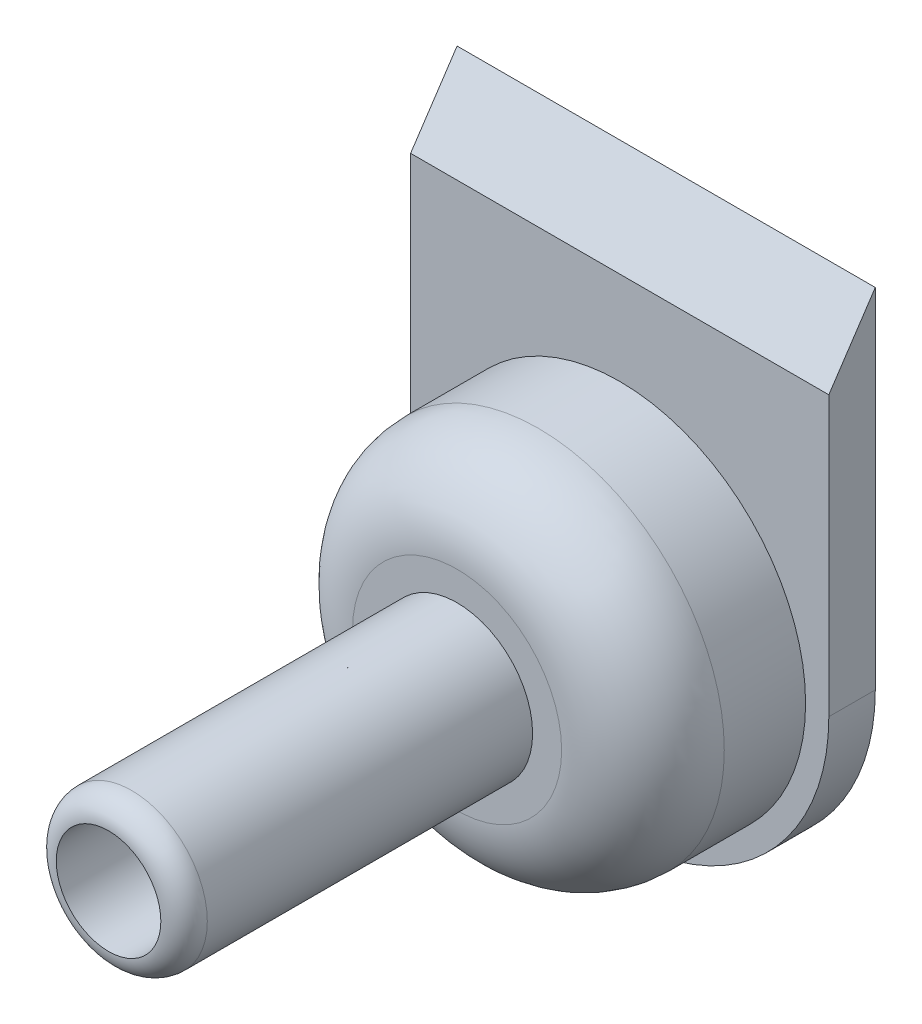
SolidWorks part; units mm, degrees
ref_plane "Płaszczyzna przednia" through (0, 0, 0) normal (0, 0, 1) x (1, 0, 0)
ref_plane "Płaszczyzna górna" through (0, 0, 0) normal (0, 1, 0) x (1, 0, 0)
ref_plane "Płaszczyzna prawa" through (0, 0, 0) normal (1, 0, 0) x (0, 0, -1)
sketch "Szkic1" plane through (0, 0, 0) normal (0, 0, 1) x (1, 0, 0)
  circle A0 centre (0, 0) radius 6.5
  dimension "D1" = 13
extrude "Dodanie-wyciągnięcie1" add sketch "Szkic1" along normal blind 30
fillet "Zaokrąglenie1" radius 2 1 edges at (6.5, 0, 30)
sketch "Szkic2" plane through (0, 0, 0) normal (0, 0, -1) x (-1, 0, 0)
  circle A0 centre (0, 0) radius 4.5
  dimension "D1" = 9
extrude "Wytnij-wyciągnięcie1" cut sketch "Szkic2" against normal blind 30
sketch "Szkic3" plane through (0, 0, 0) normal (0, 0, -1) x (-1, 0, 0)
  circle A0 centre (0, 0) radius 16
  dimension "D1" = 32
extrude "Dodanie-wyciągnięcie2" add sketch "Szkic3" along normal blind 14
fillet "Zaokrąglenie2" radius 7 1 edges at (-16, 0, 0)
sketch "Szkic4" plane through (0, 0, -14) normal (0, 0, -1) x (-1, 0, 0)
  circle A0 centre (0, 0) radius 18
  dimension "D1" = 36
extrude "Dodanie-wyciągnięcie3" add sketch "Szkic4" along normal blind 4
ref_plane "Płaszczyzna1" through (0, 30, 0) normal (0, 1, 0) x (1, 0, 0)
sketch "Szkic5" plane through (0, 30, 0) normal (0, 1, 0) x (1, 0, 0)
  line L1 (18, 14) -> (-18, 14)
  line L2 (18, 14) -> (18, 18)
  line L3 (18, 18) -> (-18, 18)
  line L4 (-18, 14) -> (-18, 18)
extrude "Dodanie-wyciągnięcie4" add sketch "Szkic5" against normal up to next
sketch "Szkic6" plane through (18, 0, 0) normal (1, 0, 0) x (0, 0, -1)
  line L0 (18, 30) -> (14, 24)
  line L1 (14, 0) -> (14, 30) construction
  line L2 (14, 24) -> (14, 30)
  line L3 (14, 30) -> (18, 30)
  dimension "D1" = 6
extrude "Wytnij-wyciągnięcie2" cut sketch "Szkic6" against normal up to next
